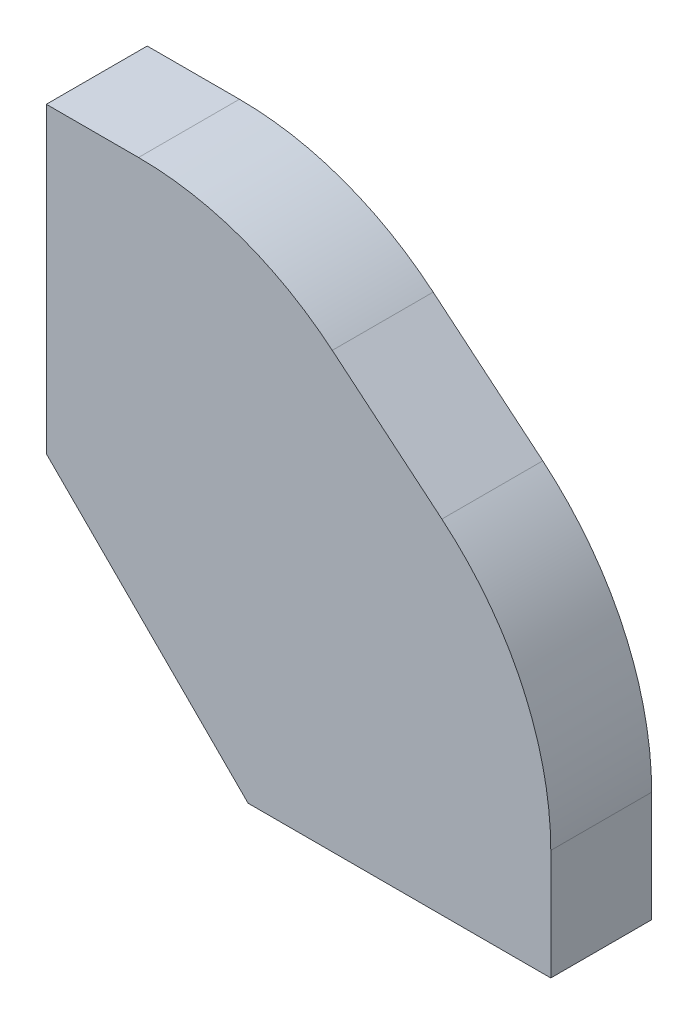
SolidWorks part; units mm, degrees
ref_plane "Plan de face" through (0, 0, 0) normal (0, 0, 1) x (1, 0, 0)
ref_plane "Plan de dessus" through (0, 0, 0) normal (0, 1, 0) x (1, 0, 0)
ref_plane "Plan de droite" through (0, 0, 0) normal (1, 0, 0) x (0, 0, -1)
sketch "Esquisse1" plane through (0, 0, 0) normal (0, 0, 1) x (1, 0, 0)
  line L0 (-20, 20) -> (0, 0)
  line L5 (-20, 20) -> (-20, -11.2753) construction
  line L7 (0, 0) -> (30, 0)
  line L8 (-20, 20) -> (-20, 50)
  line L9 (0, 50) -> (30, 25)
  line L10 (30, 25) -> (30, 0)
  line L11 (-20, 50) -> (0, 50)
  point P0 (0, 0)
  point P6 (-20, 20)
  point P7 (0, 0)
  point P10 (30, 25)
  point P11 (0, 50)
  dimension "D1" = 50
  dimension "D2" = 50
  dimension "D3" = 20
  dimension "D4" = 20
  dimension "D5" = 25
  dimension "D6" = 45
extrude "Boss.-Extru.1" add sketch "Esquisse1" along normal blind 10
fillet "Congé2" radius 30 2 edges at (30, 25, 5) (0, 50, 5)
